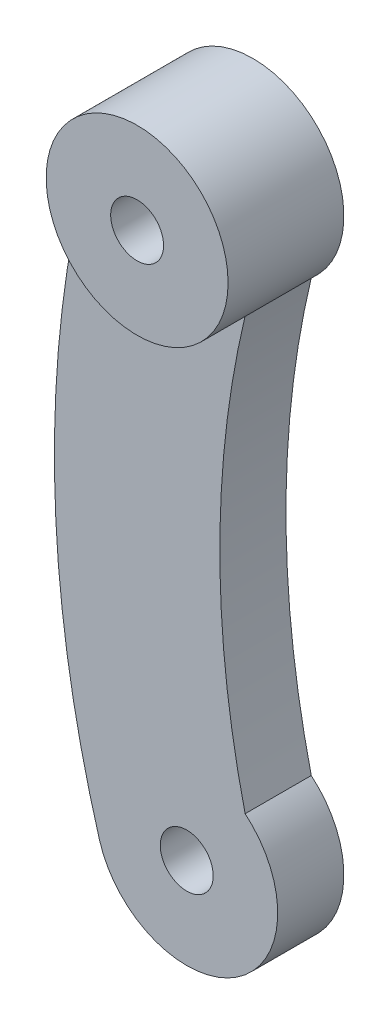
SolidWorks part; units mm, degrees
ref_plane "Ön Düzlem" through (0, 0, 0) normal (0, 0, 1) x (1, 0, 0)
ref_plane "Üst Düzlem" through (0, 0, 0) normal (0, 1, 0) x (1, 0, 0)
ref_plane "Sağ Düzlem" through (0, 0, 0) normal (1, 0, 0) x (0, 0, -1)
sketch "Çizim1" plane through (0, 0, 0) normal (0, 0, 1) x (1, 0, 0)
  line L0 (0, 34.5) -> (0, 0) construction
  line L1 (-8, 17.25) -> (34.0236, 17.25) construction
  arc A0 (-5.2737, -1.5614) -> (3.5302, 4.2175) centre (0, 0) ccw
  arc A1 (3.5302, 30.2825) -> (-5.2737, 36.0614) centre (0, 34.5) ccw
  arc A2 (-5.2737, 36.0614) -> (-5.2737, -1.5614) centre (58.2625, 17.25) ccw
  arc A3 (3.5302, 30.2825) -> (3.5302, 4.2175) centre (58.2625, 17.25) ccw
  circle A4 centre (0, 34.5) radius 1.6
  circle A5 centre (0, 0) radius 1.6
  dimension "D1" = 11
  dimension "D2" = 11
  dimension "D5" = 10
  dimension "D6" = 3.2
  dimension "D7" = 3.2
  dimension "D3" = 34.5
  dimension "D4" = 8
extrude "Yükseklik-Ekstrüzyon1" add sketch "Çizim1" along normal blind 4
sketch "Çizim3" plane through (0, 0, 4) normal (0, 0, 1) x (1, 0, 0)
  circle A0 centre (0, 34.5) radius 1.6
  circle A1 centre (0, 34.5) radius 5.5
  dimension "D1" = 3.2
  dimension "D2" = 11
extrude "Yükseklik-Ekstrüzyon3" add sketch "Çizim3" along normal blind 3
sketch "Çizim4" plane through (0, 0, 0) normal (0, 0, -1) x (-1, 0, 0)
  line L1 (2.9, 36.1743) -> (0, 37.8486)
  line L2 (0, 37.8486) -> (-2.9, 36.1743)
  line L3 (-2.9, 36.1743) -> (-2.9, 32.8257)
  line L4 (-2.9, 32.8257) -> (0, 31.1514)
  line L5 (0, 31.1514) -> (2.9, 32.8257)
  line L6 (2.9, 32.8257) -> (2.9, 36.1743)
  circle A0 centre (0, 34.5) radius 2.9 construction
  dimension "D1" = 5.8
extrude "Kes-Ekstrüzyon1" cut sketch "Çizim4" against normal blind 4
